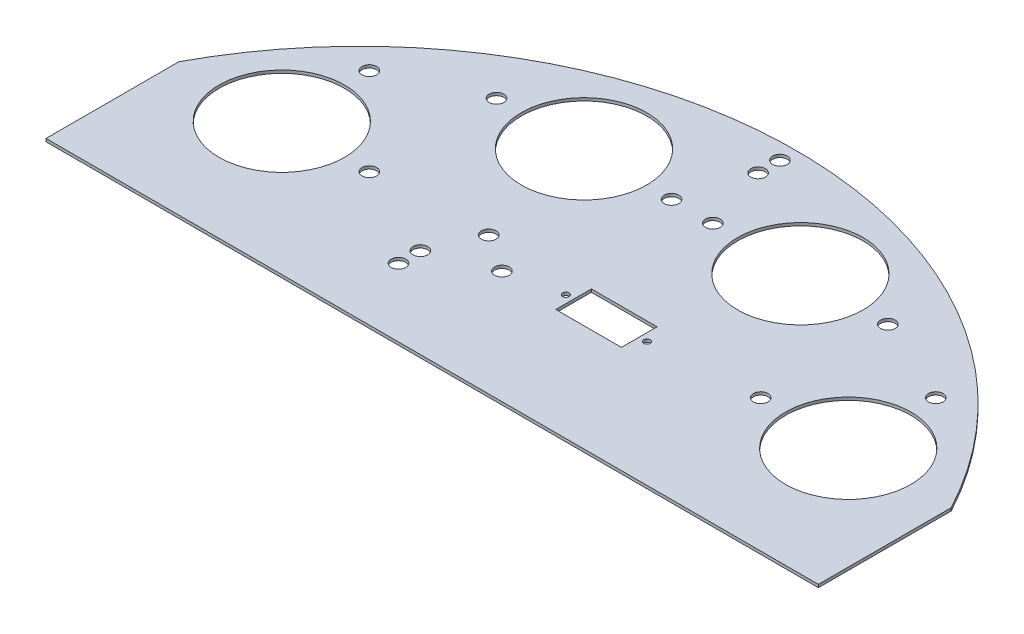
SolidWorks part; units mm, degrees
material "1060 Alloy"
ref_plane "Front Plane" through (0, 0, 0) normal (0, 0, 1) x (1, 0, 0)
ref_plane "Top Plane" through (0, 0, 0) normal (0, 1, 0) x (1, 0, 0)
ref_plane "Right Plane" through (0, 0, 0) normal (1, 0, 0) x (0, 0, -1)
sketch "Sketch3" plane through (0, 0, 0) normal (0, 1, 0) x (1, 0, 0)
  line L5 (-149.8445, -43.9726) -> (150.1555, -43.9726) construction
  line L6 (97.2375, 26.5616) -> (0.1555, -43.9726)
  line L7 (-86.3026, -18.9726) -> (-147.7465, -18.9726)
  line L8 (-132.2262, 26.5616) -> (-132.2262, -18.9726)
  line L9 (86.6136, -18.9726) -> (148.0575, -18.9726)
  line L10 (132.5372, 26.5616) -> (132.5372, -18.9726)
  line L11 (86.6136, -18.9726) -> (-86.3026, -18.9726)
  circle A10 centre (0.1555, -43.9726) radius 120 construction
  circle A11 centre (0.1555, -43.9726) radius 90 construction
  circle A12 centre (0.1555, -43.9726) radius 150
  circle A13 centre (97.2375, 26.5616) radius 21.5
  circle A14 centre (37.2375, 70.1542) radius 21.5
  circle A15 centre (-36.9265, 70.1542) radius 21.5
  circle A16 centre (-96.9265, 26.5616) radius 21.5
  point P5 (0.1555, -43.9726)
  point P9 (0.1555, -43.9726)
  point P22 (0.1555, -43.9726)
  dimension "D3" = 300
  dimension "D7" = 43
  dimension "D4" = 36
  dimension "D5" = 4
  dimension "D2" = 240
  dimension "D1" = 180
  dimension "D6" = 25
extrude "Boss-Extrude3" add sketch "Sketch3" along normal blind 1
sketch "Sketch5" plane through (0, 1, 0) normal (0, 1, 0) x (1, 0, 0)
  line L0 (37.2375, 70.1542) -> (-36.9265, 70.1542) construction
  line L1 (-36.9265, 70.1542) -> (-96.9265, 26.5616) construction
  line L2 (37.2375, 70.1542) -> (97.2375, 26.5616) construction
  circle A0 centre (97.2375, 26.5616) radius 30 construction
  circle A1 centre (37.2375, 70.1542) radius 30 construction
  circle A2 centre (-36.9265, 70.1542) radius 30 construction
  circle A3 centre (-96.9265, 26.5616) radius 30 construction
  point P12 (67.2375, 26.5616)
  point P13 (97.2375, 56.5616)
  point P14 (7.2375, 70.1542)
  point P15 (67.2375, 70.1542)
  point P16 (-6.9265, 70.1542)
  point P17 (-66.9265, 70.1542)
  point P18 (-96.9265, 56.5616)
  point P19 (-66.9265, 26.5616)
hole_wizard "Ø5.0mm Dowel Hole1" positions "Sketch8" profile "Sketch9" hole size "Ø5.0" standard "ANSI Metric" end condition through all
sketch "Sketch8" plane through (0, 0, 0) normal (0, -1, 0) x (-1, 0, 0)
  point P0 (-97.2375, 56.5616)
  point P2 (-67.2375, 26.5616)
  point P4 (-67.2375, 70.1542)
  point P6 (-7.2375, 70.1542)
  point P8 (6.9265, 70.1542)
  point P10 (66.9265, 70.1542)
  point P12 (96.9265, 56.5616)
  point P14 (66.9265, 26.5616)
sketch "Sketch9" plane through (97.2375, 0, -56.5616) normal (1, 0, 0) x (0, 0, -1)
  line L0 (0, 0) -> (0, 1)
  line L1 (0, 1) -> (2.5, 1)
  line L2 (2.5, 1) -> (2.5, 0)
  line L5 (2.5, 0) -> (0, 0)
  line L11 (0, -6.35) -> (0, 107.95) construction
  dimension "Thru Hole Dia." = 5
  dimension "Thru Hole Depth" = 1
sketch "Sketch10" plane through (0, 0, 0) normal (0, -1, 0) x (-1, 0, 0)
  line L0 (-28.4264, 17.6232) -> (-16.5209, 17.6232)
  line L1 (-27.5764, 17.6232) -> (-6.7764, 17.6232) construction
  line L2 (-28.4264, 17.6232) -> (-28.4264, 29.8232)
  line L3 (-28.4264, 29.8232) -> (-5.9264, 29.8232)
  line L4 (-5.9264, 29.8232) -> (-5.9264, 17.6232)
  line L5 (-5.9264, 17.6232) -> (-28.4264, 17.6232)
  line L6 (-5.9264, 18.4732) -> (-5.9264, 28.9732) construction
  line L7 (-6.7764, 29.8232) -> (-27.5764, 29.8232) construction
  line L8 (-28.4264, 28.9732) -> (-28.4264, 18.4732) construction
  circle A0 centre (-0.0264, 100.3613) radius 2.5
  circle A1 centre (-0.0313, 92.8613) radius 2.5
  circle A2 centre (34.7471, 4.3732) radius 2.5
  circle A3 centre (34.7471, 11.8732) radius 2.5
  circle A4 centre (14.7001, 19.7949) radius 2.5
  circle A5 centre (27.6879, 28.2546) radius 2.5
  circle A6 centre (-31.0764, 23.7232) radius 1.1
  circle A7 centre (-3.2764, 23.7232) radius 1.1
extrude "Cut-Extrude3" cut sketch "Sketch10" against normal through all contours L5 L4 L3 L2 L0 | A5 | A4 | A3 | A2 | A1 | A0 | A6 | A7
